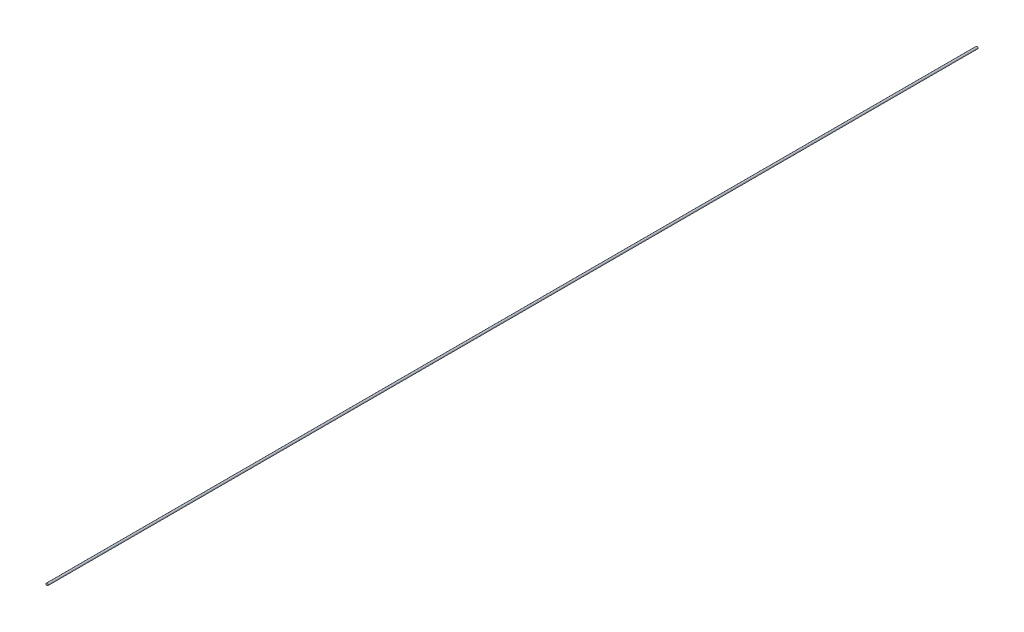
SolidWorks part; units mm, degrees
material "AISI 316 Stainless Steel Sheet (SS)"
ref_plane "Front Plane" through (0, 0, 0) normal (0, 0, 1) x (1, 0, 0)
ref_plane "Top Plane" through (0, 0, 0) normal (0, 1, 0) x (1, 0, 0)
ref_plane "Right Plane" through (0, 0, 0) normal (1, 0, 0) x (0, 0, -1)
sketch "Sketch1" plane through (0, 0, 0) normal (0, 0, 1) x (1, 0, 0)
  circle A0 centre (0, 0) radius 0.15
  dimension "D1" = 0.3
extrude "Boss-Extrude1" add sketch "Sketch1" along normal blind 133
